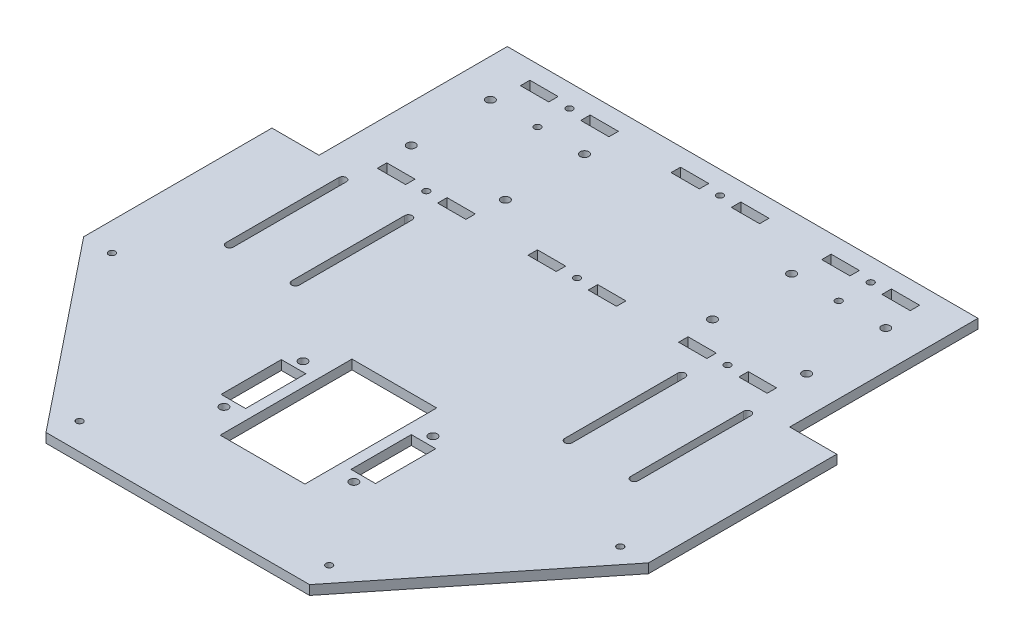
SolidWorks part; units mm, degrees
ref_plane "前基準面" through (0, 0, 0) normal (0, 0, 1) x (1, 0, 0)
ref_plane "上基準面" through (0, 0, 0) normal (0, 1, 0) x (1, 0, 0)
ref_plane "右基準面" through (0, 0, 0) normal (1, 0, 0) x (0, 0, -1)
sketch "草圖2" plane through (0, 0, 0) normal (0, 1, 0) x (1, 0, 0)
  line L0 (0, 150) -> (0, 0) construction
  line L1 (-150, 150) -> (150, 150)
  line L2 (-150, 150) -> (-150, -50)
  line L3 (-70, -150) -> (70, -150)
  line L4 (150, 150) -> (150, -50)
  line L5 (-150, 150) -> (150, -150) construction
  line L6 (-150, -150) -> (150, 150) construction
  line L7 (-105, 121) -> (-55, 121) construction
  line L8 (-105, 121) -> (-105, 79) construction
  line L9 (-105, 79) -> (-55, 79) construction
  line L10 (-55, 121) -> (-55, 79) construction
  line L11 (-105, 121) -> (-55, 79) construction
  line L12 (-105, 79) -> (-55, 121) construction
  line L13 (55, 121) -> (55, 79) construction
  line L14 (105, 79) -> (55, 79) construction
  line L15 (105, 121) -> (105, 79) construction
  line L16 (105, 121) -> (55, 121) construction
  line L17 (-150, -50) -> (-70, -150)
  line L18 (150, -50) -> (70, -150)
  line L19 (-150, -50) -> (-150, -150) construction
  line L20 (-150, -150) -> (-70, -150) construction
  line L21 (150, -50) -> (150, -150) construction
  line L22 (150, -150) -> (70, -150) construction
  circle A0 centre (-105, 121) radius 2.25
  circle A1 centre (-105, 79) radius 2.25
  circle A2 centre (-55, 79) radius 2.25
  circle A3 centre (-55, 121) radius 2.25
  circle A4 centre (55, 121) radius 2.25
  circle A5 centre (55, 79) radius 2.25
  circle A6 centre (105, 121) radius 2.25
  circle A7 centre (105, 79) radius 2.25
  point P0 (0, 0)
  point P6 (-80, 100)
  dimension "D7" = 4.5
  dimension "D1" = 42
  dimension "D2" = 50
  dimension "D3" = 50
  dimension "D4" = 70
  dimension "D5" = 300
  dimension "D6" = 300
  dimension "D8" = 100
  dimension "D9" = 80
extrude "填料-伸長2" add sketch "草圖2" along normal blind 5
sketch "草圖3" plane through (0, 5, 0) normal (0, 1, 0) x (1, 0, 0)
  line L0 (0, 150) -> (0, 0) construction
  line L1 (-150, 150) -> (-125, 150)
  line L2 (-150, 150) -> (-150, 50)
  line L3 (-150, 50) -> (-125, 50)
  line L4 (-125, 150) -> (-125, 50)
  line L5 (150, 150) -> (-150, 150) construction
  line L6 (125, 150) -> (125, 50)
  line L7 (150, 50) -> (125, 50)
  line L8 (150, 150) -> (150, 50)
  line L9 (150, 150) -> (125, 150)
  dimension "D1" = 25
  dimension "D2" = 100
extrude "除料-伸長1" cut sketch "草圖3" against normal blind 5
sketch "草圖4" plane through (0, 5, 0) normal (0, 1, 0) x (1, 0, 0)
  line L0 (-160.2953, 15) -> (151.001, 15) construction
  line L1 (-107.5, 35) -> (-72.5, 35) construction
  line L2 (-107.5, 35) -> (-107.5, -5) construction
  line L3 (-107.5, -5) -> (-72.5, -5) construction
  line L4 (-72.5, 35) -> (-72.5, -5) construction
  line L5 (-107.5, 35) -> (-72.5, -5) construction
  line L6 (-107.5, -5) -> (-72.5, 35) construction
  line L7 (-150, 50) -> (-150, -50) construction
  line L8 (-107.5, 45) -> (-107.5, -15) construction
  line L9 (-107.5, 45) -> (-107.5, -15) construction
  line L10 (-90, -5) -> (-90, 58.5317) construction
  line L11 (-105.5, 45) -> (-105.5, -15)
  line L12 (-109.5, 45) -> (-109.5, -15)
  line L13 (-72.5, 45) -> (-72.5, -15) construction
  line L14 (-74.5, 45) -> (-74.5, -15)
  line L15 (-70.5, 45) -> (-70.5, -15)
  line L16 (0, 60.0422) -> (0, -21.3854) construction
  line L17 (107.5, 45) -> (107.5, -15) construction
  line L18 (105.5, 45) -> (105.5, -15)
  line L19 (109.5, 45) -> (109.5, -15)
  line L20 (72.5, 45) -> (72.5, -15) construction
  line L21 (74.5, 45) -> (74.5, -15)
  line L22 (70.5, 45) -> (70.5, -15)
  arc A0 (-105.5, 45) -> (-109.5, 45) centre (-107.5, 45) ccw
  arc A1 (-109.5, -15) -> (-105.5, -15) centre (-107.5, -15) ccw
  arc A2 (-74.5, 45) -> (-70.5, 45) centre (-72.5, 45) cw
  arc A3 (-70.5, -15) -> (-74.5, -15) centre (-72.5, -15) cw
  arc A4 (105.5, 45) -> (109.5, 45) centre (107.5, 45) cw
  arc A5 (109.5, -15) -> (105.5, -15) centre (107.5, -15) cw
  arc A6 (74.5, 45) -> (70.5, 45) centre (72.5, 45) ccw
  arc A7 (70.5, -15) -> (74.5, -15) centre (72.5, -15) ccw
  point P0 (-90, 15)
  point P12 (-107.5, 15)
  point P21 (-72.5, 15)
  point P30 (107.5, 15)
  point P37 (72.5, 15)
  dimension "D7" = 2
  dimension "D1" = 40
  dimension "D2" = 35
  dimension "D3" = 15
  dimension "D4" = 60
  dimension "D5" = 10
  dimension "D6" = 10
extrude "除料-伸長2" cut sketch "草圖4" against normal blind 5
sketch "草圖5" plane through (0, 5, 0) normal (0, 1, 0) x (1, 0, 0)
  line L0 (0, 0) -> (0, 91.4247) construction
  line L1 (-89.289, 62) -> (111.0725, 62) construction
  line L2 (-105, 121) -> (-105, 79) construction
  line L3 (-105, 79) -> (-105, 100) construction
  line L4 (-105, 100) -> (63.1861, 100) construction
  line L5 (8.5, 59.5) -> (8.5, 64.5)
  line L6 (-23.5, 59.5) -> (-8.5, 59.5)
  line L7 (-23.5, 59.5) -> (-23.5, 64.5)
  line L8 (-23.5, 64.5) -> (-8.5, 64.5)
  line L9 (-8.5, 59.5) -> (-8.5, 64.5)
  line L10 (-23.5, 59.5) -> (-8.5, 64.5) construction
  line L11 (-23.5, 64.5) -> (-8.5, 59.5) construction
  line L12 (23.5, 59.5) -> (8.5, 59.5)
  line L13 (23.5, 59.5) -> (23.5, 64.5)
  line L14 (23.5, 64.5) -> (8.5, 64.5)
  line L15 (-80, 75.6029) -> (-80, 51.5667) construction
  line L16 (-103.5, 59.5) -> (-88.5, 59.5)
  line L17 (-103.5, 59.5) -> (-103.5, 64.5)
  line L18 (-103.5, 64.5) -> (-88.5, 64.5)
  line L19 (-88.5, 59.5) -> (-88.5, 64.5)
  line L20 (-103.5, 59.5) -> (-88.5, 64.5) construction
  line L21 (-103.5, 64.5) -> (-88.5, 59.5) construction
  line L22 (-71.5, 59.5) -> (-71.5, 64.5)
  line L23 (-56.5, 59.5) -> (-71.5, 59.5)
  line L24 (-56.5, 59.5) -> (-56.5, 64.5)
  line L25 (-56.5, 64.5) -> (-71.5, 64.5)
  line L26 (56.5, 59.5) -> (56.5, 64.5)
  line L27 (56.5, 59.5) -> (71.5, 59.5)
  line L28 (71.5, 59.5) -> (71.5, 64.5)
  line L29 (56.5, 64.5) -> (71.5, 64.5)
  line L30 (88.5, 59.5) -> (88.5, 64.5)
  line L31 (103.5, 59.5) -> (88.5, 59.5)
  line L32 (103.5, 59.5) -> (103.5, 64.5)
  line L33 (103.5, 64.5) -> (88.5, 64.5)
  line L34 (-103.5, 135.5) -> (-88.5, 140.5) construction
  line L35 (-103.5, 140.5) -> (-88.5, 135.5) construction
  line L37 (-23.5, 135.5) -> (-8.5, 140.5) construction
  line L38 (-23.5, 140.5) -> (-8.5, 135.5) construction
  line L40 (0, 200) -> (0, 108.5753) construction
  line L41 (103.5, 135.5) -> (88.5, 135.5)
  line L42 (103.5, 140.5) -> (103.5, 135.5)
  line L43 (103.5, 140.5) -> (88.5, 140.5)
  line L44 (88.5, 140.5) -> (88.5, 135.5)
  line L45 (56.5, 135.5) -> (71.5, 135.5)
  line L46 (71.5, 140.5) -> (71.5, 135.5)
  line L47 (56.5, 140.5) -> (71.5, 140.5)
  line L48 (56.5, 140.5) -> (56.5, 135.5)
  line L49 (-56.5, 135.5) -> (-71.5, 135.5)
  line L50 (-56.5, 140.5) -> (-56.5, 135.5)
  line L51 (-56.5, 140.5) -> (-71.5, 140.5)
  line L52 (-71.5, 140.5) -> (-71.5, 135.5)
  line L53 (-88.5, 140.5) -> (-88.5, 135.5)
  line L54 (-103.5, 135.5) -> (-88.5, 135.5)
  line L55 (-103.5, 140.5) -> (-103.5, 135.5)
  line L56 (-103.5, 140.5) -> (-88.5, 140.5)
  line L57 (23.5, 135.5) -> (8.5, 135.5)
  line L58 (23.5, 140.5) -> (23.5, 135.5)
  line L59 (23.5, 140.5) -> (8.5, 140.5)
  line L60 (-8.5, 140.5) -> (-8.5, 135.5)
  line L61 (-23.5, 135.5) -> (-8.5, 135.5)
  line L62 (-23.5, 140.5) -> (-23.5, 135.5)
  line L63 (-23.5, 140.5) -> (-8.5, 140.5)
  line L64 (8.5, 140.5) -> (8.5, 135.5)
  circle A0 centre (0, 62) radius 1.75
  circle A1 centre (-80, 62) radius 1.75
  circle A2 centre (80, 62) radius 1.75
  circle A3 centre (80, 138) radius 1.75
  circle A4 centre (-80, 138) radius 1.75
  circle A5 centre (0, 138) radius 1.75
  point P13 (-16, 62)
  point P24 (-96, 62)
  point P81 (-96, 138)
  point P82 (-16, 138)
  dimension "D2" = 3.5
  dimension "D6" = 3.5
  dimension "D1" = 62
  dimension "D3" = 5
  dimension "D4" = 15
  dimension "D5" = 16
  dimension "D7" = 15
  dimension "D8" = 5
  dimension "D9" = 16
  dimension "D10" = 80
extrude "除料-伸長3" cut sketch "草圖5" against normal through all
sketch "草圖7" plane through (0, 5, 0) normal (0, 1, 0) x (1, 0, 0)
  line L0 (0, 0) -> (0, -150) construction
  line L1 (-70, -150) -> (70, -150) construction
  line L2 (28, -86) -> (28, -54)
  line L3 (-34.5, -91) -> (34.5, -91) construction
  line L4 (-34.5, -91) -> (-34.5, -49) construction
  line L5 (-34.5, -49) -> (34.5, -49) construction
  line L6 (34.5, -91) -> (34.5, -49) construction
  line L7 (-34.5, -91) -> (34.5, -49) construction
  line L8 (-34.5, -49) -> (34.5, -91) construction
  line L9 (-22.5, -105) -> (22.5, -105)
  line L10 (-22.5, -105) -> (-22.5, -35)
  line L11 (-22.5, -35) -> (22.5, -35)
  line L12 (22.5, -105) -> (22.5, -35)
  line L13 (-22.5, -105) -> (22.5, -35) construction
  line L14 (-22.5, -35) -> (22.5, -105) construction
  line L15 (-41, -86) -> (-28, -86)
  line L16 (-41, -86) -> (-41, -54)
  line L17 (-41, -54) -> (-28, -54)
  line L18 (-28, -86) -> (-28, -54)
  line L19 (-41, -86) -> (-28, -54) construction
  line L20 (-41, -54) -> (-28, -86) construction
  line L21 (41, -86) -> (28, -86)
  line L22 (41, -86) -> (41, -54)
  line L23 (41, -54) -> (28, -54)
  circle A0 centre (-34.5, -49) radius 2.25
  circle A1 centre (-34.5, -91) radius 2.25
  circle A2 centre (34.5, -91) radius 2.25
  circle A3 centre (34.5, -49) radius 2.25
  point P5 (0, -70)
  point P10 (0, -70)
  point P19 (-34.5, -70)
  dimension "D6" = 4.5
  dimension "D1" = 69
  dimension "D2" = 42
  dimension "D3" = 80
  dimension "D4" = 45
  dimension "D5" = 70
  dimension "D7" = 13
  dimension "D8" = 32
extrude "除料-伸長4" cut sketch "草圖7" against normal blind 10
sketch "草圖8" plane through (0, 5, 0) normal (0, 1, 0) x (1, 0, 0)
  line L0 (-105, 121) -> (-55, 121) construction
  line L1 (0, 138) -> (0, 62) construction
  line L2 (-150, -50) -> (-135, -50) construction
  line L3 (-135, -50) -> (-55, -150) construction
  line L4 (-70, -150) -> (70, -150) construction
  line L5 (-55, -150) -> (-70, -150) construction
  line L6 (-70, -150) -> (-150, -50) construction
  circle A0 centre (-55, 121) radius 2.25 construction
  circle A1 centre (-105, 121) radius 2.25 construction
  circle A2 centre (-55, 121) radius 2.25 construction
  circle A3 centre (-105, 121) radius 2.25 construction
  circle A4 centre (-80, 121) radius 1.75
  circle A5 centre (80, 121) radius 1.75
  circle A6 centre (-135, -50) radius 1.75
  circle A7 centre (-66.2835, -135.8956) radius 1.75
  circle A8 centre (135, -50) radius 1.75
  circle A9 centre (66.2835, -135.8956) radius 1.75
  dimension "D1" = 3.5
  dimension "D3" = 3.5
  dimension "D4" = 3.5
  dimension "D5" = 110
  dimension "D2" = 15
extrude "除料-伸長5" cut sketch "草圖8" against normal through all
